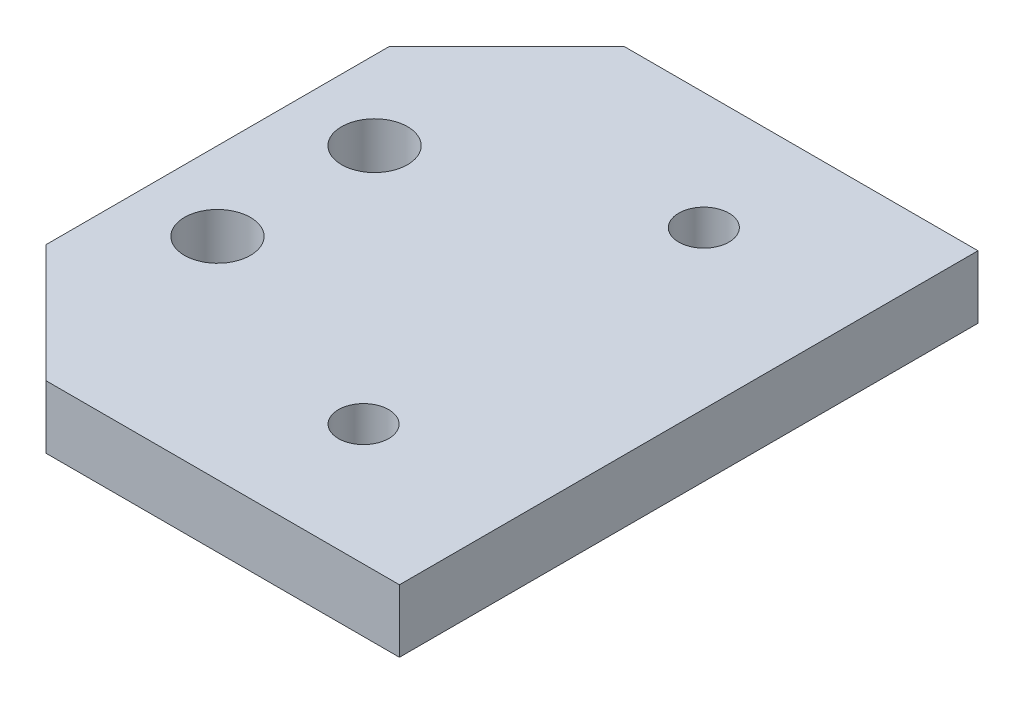
SolidWorks part; units mm, degrees
ref_plane "Front Plane" through (0, 0, 0) normal (0, 0, 1) x (1, 0, 0)
ref_plane "Top Plane" through (0, 0, 0) normal (0, 1, 0) x (1, 0, 0)
ref_plane "Right Plane" through (0, 0, 0) normal (1, 0, 0) x (0, 0, -1)
sketch "Sketch1" plane through (0, 0, 0) normal (0, 1, 0) x (1, 0, 0)
  line L0 (5, 23.415) -> (5, 13.415) construction
  line L1 (0, 0) -> (30, 0)
  line L2 (0, 0) -> (0, 36.83)
  line L3 (0, 36.83) -> (30, 36.83)
  line L4 (30, 0) -> (30, 36.83)
  line L5 (0, 28.615) -> (10, 28.615) construction
  line L6 (0, 28.615) -> (0, 8.215) construction
  line L7 (0, 8.215) -> (10, 8.215) construction
  line L8 (10, 28.615) -> (10, 8.215) construction
  line L9 (0, 28.615) -> (10, 8.215) construction
  line L10 (0, 8.215) -> (10, 28.615) construction
  circle A0 centre (5, 23.415) radius 2.1
  circle A1 centre (5, 13.415) radius 2.1
  point P9 (5, 18.415)
  point P10 (0, 18.415)
  point P11 (0, 18.415)
  dimension "D5" = 4.2
  dimension "D8" = 5
  dimension "D1" = 36.83
  dimension "D2" = 30
  dimension "D3" = 20.4
  dimension "D4" = 10
  dimension "D6" = 5.2
  dimension "D7" = 5.2
extrude "Boss-Extrude1" add sketch "Sketch1" along normal blind 4
chamfer "Chamfer1" distance 7.5 angle 45 2 edges at (0, 2, -36.83) (0, 2, 0)
sketch "Sketch2" plane through (0, 4, 0) normal (0, 1, 0) x (1, 0, 0)
  line L0 (20, 29.3778) -> (20, 7.7163) construction
  line L3 (10, 8.215) -> (10, 28.615) construction
  line L4 (10, 8.215) -> (10, 28.615) construction
  circle A0 centre (20, 29.3778) radius 1.6
  circle A1 centre (20, 7.7163) radius 1.6
  dimension "D1" = 3.2
  dimension "D2" = 10
extrude "Cut-Extrude1" cut sketch "Sketch2" against normal through all
